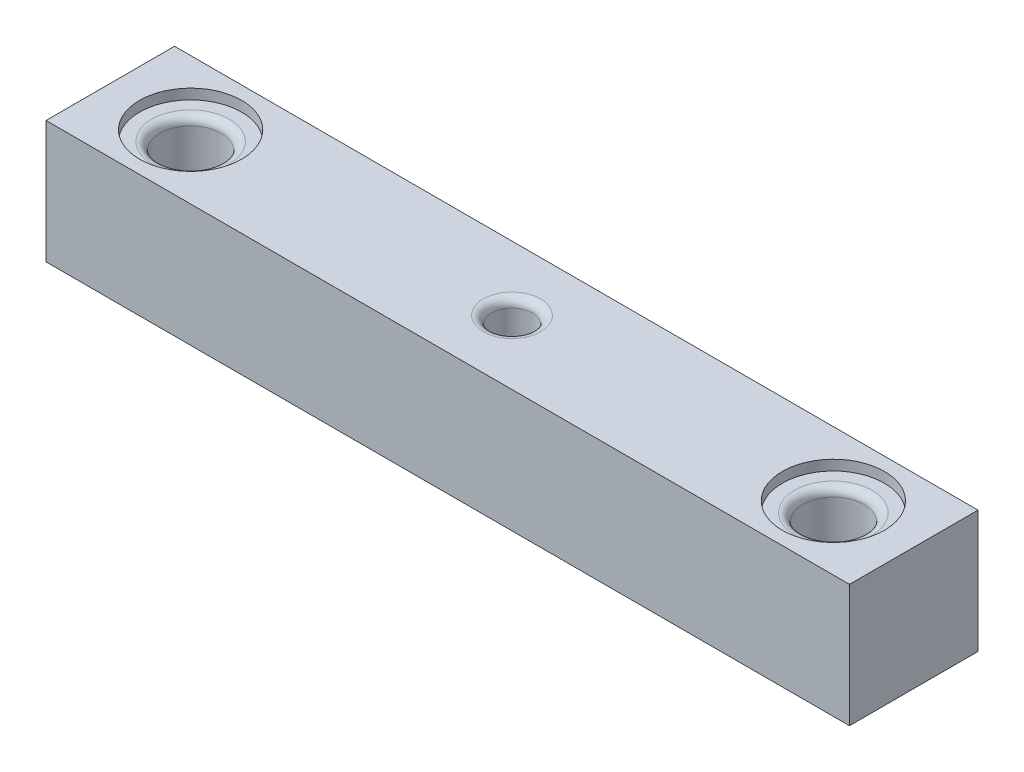
SolidWorks part; units mm, degrees
material "6061 Alloy"
ref_plane "Front Plane" through (0, 0, 0) normal (0, 0, 1) x (1, 0, 0)
ref_plane "Top Plane" through (0, 0, 0) normal (0, 1, 0) x (1, 0, 0)
ref_plane "Right Plane" through (0, 0, 0) normal (1, 0, 0) x (0, 0, -1)
sketch "Sketch1" plane through (0, 0, 0) normal (0, 1, 0) x (1, 0, 0)
  line L0 (125, 0) -> (-125, 0)
  line L1 (-125, 20) -> (125, 20)
  line L2 (-125, 20) -> (-125, -20)
  line L3 (-125, -20) -> (125, -20)
  line L4 (125, 20) -> (125, -20)
  line L5 (-125, 20) -> (125, -20) construction
  line L6 (-125, -20) -> (125, 20) construction
  line L7 (-100, -20) -> (100, -20)
  line L8 (-100, -20) -> (-100, 20)
  line L9 (-100, 20) -> (100, 20)
  line L10 (100, -20) -> (100, 20)
  line L11 (-100, -20) -> (100, 20) construction
  line L12 (-100, 20) -> (100, -20) construction
  circle A0 centre (-100, 0) radius 15.875
  circle A1 centre (100, 0) radius 15.875
  circle A2 centre (-100, 0) radius 9.525
  circle A3 centre (100, 0) radius 9.525
  point P0 (0, 0)
  point P6 (0, 0)
  point P14 (0, 0)
  dimension "D4" = 31.75
  dimension "D5" = 31.75
  dimension "D6" = 19.05
  dimension "D7" = 19.05
  dimension "D1" = 40
  dimension "D2" = 250
  dimension "D3" = 200
extrude "Boss-Extrude1" add sketch "Sketch1" along normal blind 38.1 contours A0 L8 L1 L2 L0 | L8 A0 L0 | L0 A0 L8 | L8 A0 L0 | L0 A0 L8 | A0 L0 L2 L3 L8 | A1 L10 L1 L8 A0 L0 | A1 L0 A0 L8 L3 L10 | L0 A1 L10 | L10 A1 L0 | L0 A1 L10 | L10 A1 L0 | A1 L10 L3 L4 L0 | A1 L0 L4 L1 L10
sketch "Sketch3" plane through (0, 38.1, 0) normal (0, 1, 0) x (1, 0, 0)
  circle A0 centre (-100, 0) radius 15.875
  circle A1 centre (100, 0) radius 15.875
extrude "Cut-Extrude1" cut sketch "Sketch3" against normal blind 3.175
sketch "Sketch4" plane through (0, 38.1, 0) normal (0, 1, 0) x (1, 0, 0)
  circle A0 centre (0, 0) radius 6.35
  dimension "D1" = 12.7
extrude "Cut-Extrude2" cut sketch "Sketch4" against normal through all
fillet "Fillet1" radius 2.54 3 edges at (100, 34.925, 9.525) (-100, 34.925, 9.525) (0, 38.1, 6.35)
equation "\"w\"= .04"
equation "\"dist\"= .2"
equation "\"E\"= 68.9 * ( 10 ^ 9 )"
equation "\"del\"= 0.0001"
equation "\"F\"= 2000"
equation "\"I\"= ( \"F\" * ( \"dist\" ^ 3 ) ) / ( 48 * \"E\" * \"del\" )"
equation "\"h\"= ( ( 12 * \"I\" ) / \"w\" ) ^ ( 1 / 3 )"
equation "\"b\"= \"w\" / 0.0254"
equation "\"dis\"= \"dist\" / 0.0254"
equation "\"L\"= .25 / 0.0254"
equation "\"t\"= \"h\" / 0.0254"
equation "\"d1\"= 1 + ( 1 / 4 )"
equation "\"D2@Sketch1\"=\"L\""
equation "\"D1@Sketch1\"=\"b\""
equation "\"D3@Sketch1\"=\"dis\""
equation "\"D4@Sketch1\"=\"d1\""
equation "\"D5@Sketch1\"=\"d1\""
equation "\"D1@Boss-Extrude1\"=1.5"
equation "\"t2\"= 1 / 8"
equation "\"D1@Cut-Extrude1\"=\"t2\""
equation "\"d2\"= 3 / 4"
equation "\"D7@Sketch1\"=\"d2\""
equation "\"D6@Sketch1\"=\"d2\""
